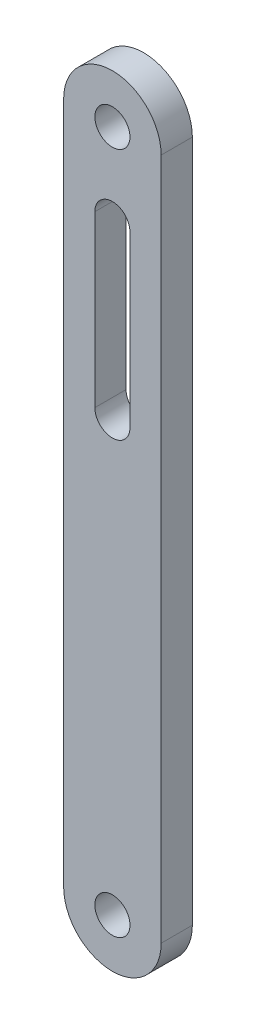
SolidWorks part; units mm, degrees
ref_plane "Front Plane" through (0, 0, 0) normal (0, 0, 1) x (1, 0, 0)
ref_plane "Top Plane" through (0, 0, 0) normal (0, 1, 0) x (1, 0, 0)
ref_plane "Right Plane" through (0, 0, 0) normal (1, 0, 0) x (0, 0, -1)
sketch "Sketch1" plane through (0, 0, 0) normal (0, 0, 1) x (1, 0, 0)
  line L0 (0, -35) -> (0, 35) construction
  line L5 (-5, -35) -> (-5, 35)
  line L6 (5, -35) -> (5, 35)
  line L8 (0, 26.5744) -> (0, 9.1706) construction
  line L9 (1.8, 26.5744) -> (1.8, 9.1706)
  line L10 (-1.8, 26.5744) -> (-1.8, 9.1706)
  circle A0 centre (0, 35) radius 1.8
  circle A1 centre (0, -35) radius 1.8
  arc A2 (1.8, 26.5744) -> (-1.8, 26.5744) centre (0, 26.5744) ccw
  arc A3 (-1.8, 9.1706) -> (1.8, 9.1706) centre (0, 9.1706) ccw
  arc A4 (-5, -35) -> (5, -35) centre (0, -35) ccw
  arc A5 (5, 35) -> (-5, 35) centre (0, 35) ccw
  point P0 (0, 0)
  point P2 (0, 0)
  point P11 (0, 37.85)
  point P13 (0, 0)
  point P16 (0, 17.8725)
  dimension "D3" = 3.6
  dimension "D5" = 3.6
  dimension "D1" = 3.2
  dimension "D6" = 5
  dimension "D7" = 17.8725
  dimension "D2" = 17.4038
  dimension "D4" = 35
extrude "Boss-Extrude1" add sketch "Sketch1" along normal blind 3.2
